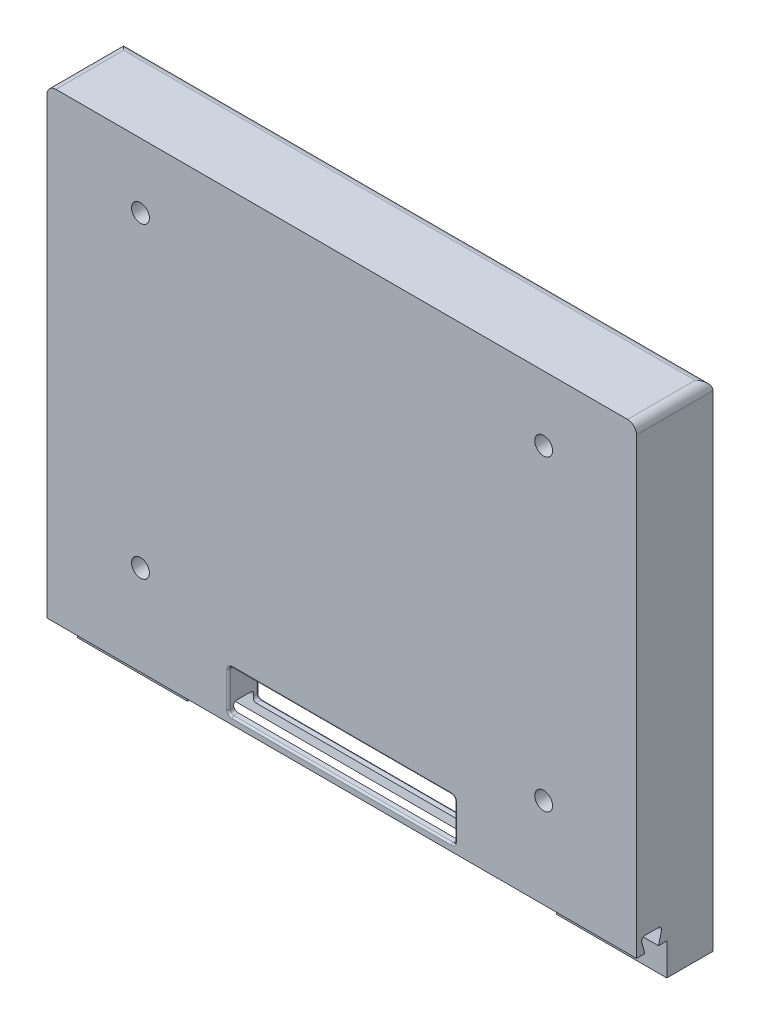
SolidWorks part; units mm, degrees
material "PLA"
ref_plane "Front Plane" through (0, 0, 0) normal (0, 0, 1) x (1, 0, 0)
ref_plane "Top Plane" through (0, 0, 0) normal (0, 1, 0) x (1, 0, 0)
ref_plane "Right Plane" through (0, 0, 0) normal (1, 0, 0) x (0, 0, -1)
sketch "Sketch1" plane through (0, 0, 0) normal (0, 0, 1) x (1, 0, 0)
  line L0 (0, 0) -> (0, -138.8145) construction
  line L1 (-82.55, -90.8019) -> (82.55, -90.8019)
  line L2 (-82.55, -90.8019) -> (-82.55, 9.1981)
  line L3 (-82.55, 9.1981) -> (82.55, 9.1981)
  line L4 (82.55, -90.8019) -> (82.55, 9.1981)
  point P7 (0, -90.8019)
  dimension "D1" = 165.1
  dimension "D2" = 100
extrude "Boss-Extrude1" add sketch "Sketch1" along normal blind 5
sketch "Sketch4" plane through (0, 0, 0) normal (0, 0, -1) x (-1, 0, 0)
  line L4 (-82.55, 9.1981) -> (-82.55, -90.8019)
  line L5 (-82.55, -90.8019) -> (82.55, -90.8019)
  line L6 (82.55, -90.8019) -> (82.55, 9.1981)
  line L7 (82.55, 9.1981) -> (-82.55, 9.1981)
  line L8 (-82.55, 9.1981) -> (-82.55, -90.8019)
  line L9 (-82.55, -90.8019) -> (82.55, -90.8019)
  line L10 (82.55, -90.8019) -> (82.55, 9.1981)
  line L11 (82.55, 9.1981) -> (-82.55, 9.1981)
  dimension "D1" = 0
extrude "Boss-Extrude2" add sketch "Sketch4" along normal blind 3.5
ref_plane "Plane1" through (-27.79, 0, 0) normal (-1, 0, 0) x (0, 0, 1)
sketch "Sketch10" plane through (0, -90.8019, 0) normal (0, -1, 0) x (1, 0, 0)
  line L4 (-82.55, 5) -> (-82.55, -3.5)
  line L5 (-82.55, -3.5) -> (82.55, -3.5)
  line L6 (82.55, -3.5) -> (82.55, 5)
  line L7 (82.55, 5) -> (-82.55, 5)
  line L8 (-82.55, 5) -> (-82.55, -3.5)
  line L9 (-82.55, -3.5) -> (82.55, -3.5)
  line L10 (82.55, -3.5) -> (82.55, 5)
  line L11 (82.55, 5) -> (-82.55, 5)
  dimension "D1" = 0
extrude "Boss-Extrude4" add sketch "Sketch10" along normal blind 17
sketch "Sketch11" plane through (0, 0, -3.5) normal (0, 0, -1) x (-1, 0, 0)
  line L0 (0, 9.1981) -> (0, -107.8019) construction
  line L1 (82.55, 9.1981) -> (-82.55, 9.1981) construction
  line L2 (82.55, -107.8019) -> (-82.55, -107.8019) construction
  line L3 (-82.55, -49.3019) -> (82.55, -49.3019) construction
  line L4 (-82.55, 9.1981) -> (-82.55, -107.8019) construction
  line L5 (82.55, -107.8019) -> (82.55, 9.1981) construction
  line L7 (-51.7, -3.8519) -> (51.7, -3.8519)
  line L8 (-51.7, -3.8519) -> (-51.7, -94.7519)
  line L9 (-51.7, -94.7519) -> (51.7, -94.7519)
  line L10 (51.7, -3.8519) -> (51.7, -94.7519)
  point P16 (0, -3.8519)
  point P17 (-51.7, -49.3019)
  dimension "D1" = 103.4
  dimension "D2" = 90.9
extrude "Cut-Extrude6" cut sketch "Sketch11" against normal blind 6
sketch "Sketch12" plane through (0, 0, -3.5) normal (0, 0, -1) x (-1, 0, 0)
  line L0 (82.55, -107.8019) -> (82.55, 9.1981) construction
  line L1 (-82.55, 9.1981) -> (82.55, 9.1981)
  line L2 (-82.55, 9.1981) -> (-82.55, -3.8519)
  line L3 (-82.55, -3.8519) -> (82.55, -3.8519)
  line L4 (82.55, 9.1981) -> (82.55, -3.8519)
  line L5 (51.7, -3.8519) -> (-51.7, -3.8519) construction
  dimension "D1" = 0
extrude "Boss-Extrude5" add sketch "Sketch12" along normal blind 12.95
sketch "Sketch13" plane through (0, 9.1981, 0) normal (0, 1, 0) x (1, 0, 0)
  line L0 (82.55, -5) -> (82.55, 16.45) construction
  line L1 (-82.55, 16.45) -> (82.55, 16.45)
  line L2 (-82.55, 16.45) -> (-82.55, -5)
  line L3 (-82.55, -5) -> (82.55, -5)
  line L4 (82.55, 16.45) -> (82.55, -5)
  dimension "D1" = 21.45
extrude "Boss-Extrude6" add sketch "Sketch13" along normal blind 9.75
sketch "Sketch14" plane through (0, 0, -3.5) normal (0, 0, -1) x (-1, 0, 0)
  line L0 (-51.7, -106.5019) -> (-51.7, -119.5519)
  line L7 (-82.55, -3.8519) -> (-82.55, -119.5519)
  line L10 (-82.55, -3.8519) -> (82.55, -3.8519) construction
  line L16 (-51.7, -3.8519) -> (-82.55, -3.8519)
  line L23 (-51.7, -106.5019) -> (-51.7, -3.8519)
  line L24 (-82.55, -119.5519) -> (-51.7, -119.5519)
  line L26 (82.55, -119.5519) -> (51.7, -119.5519)
  line L27 (82.55, -119.5519) -> (82.55, -3.8519)
  line L28 (82.55, -3.8519) -> (51.7, -3.8519)
  line L29 (51.7, -119.5519) -> (51.7, -3.8519)
  dimension "D1" = 115.7
  dimension "D2" = 115.7
extrude "Boss-Extrude7" add sketch "Sketch14" along normal up to surface (12.95 mm away) up to face at (0, 7.5481, -16.45)
sketch "Sketch15" plane through (0, 0, -16.45) normal (0, 0, -1) x (-1, 0, 0)
  circle A0 centre (56.3625, -85.2719) radius 1.35 construction
  circle A1 centre (56.3625, 0.8106) radius 1.35 construction
  circle A2 centre (-56.5625, 0.8106) radius 1.35 construction
  circle A3 centre (-56.5625, -85.2719) radius 1.35 construction
  circle A4 centre (56.3625, -85.2719) radius 1.35
  circle A5 centre (56.3625, 0.8106) radius 1.35
  circle A6 centre (-56.5625, 0.8106) radius 1.35
  circle A7 centre (-56.5625, -85.2719) radius 1.35
extrude "Cut-Extrude7" cut sketch "Sketch15" against normal blind 8.65
sketch "Sketch16" plane through (0, 0, -7.8) normal (0, 0, -1) x (-1, 0, 0)
  circle A0 centre (56.3625, 0.8106) radius 2.5
  circle A1 centre (-56.5625, 0.8106) radius 2.5
  circle A2 centre (-56.5625, -85.2719) radius 2.5
  circle A3 centre (56.3625, -85.2719) radius 2.5
  dimension "D1" = 5
  dimension "D2" = 5
extrude "Cut-Extrude8" cut sketch "Sketch16" against normal through all
sketch "Sketch17" plane through (0, -107.8019, 0) normal (0, -1, 0) x (1, 0, 0)
  line L0 (82.55, -3.5) -> (82.55, 5) construction
  line L1 (-82.55, 5) -> (82.55, 5)
  line L2 (-82.55, 5) -> (-82.55, -3.5)
  line L3 (-82.55, -3.5) -> (82.55, -3.5)
  line L4 (82.55, 5) -> (82.55, -3.5)
  dimension "D1" = 8.5
fillet "Fillet1" radius 2.5 3 edges at (82.55, 18.9481, -5.725) (-82.55, 18.9481, -5.725) (0, 18.9481, -16.45)
extrude "Boss-Extrude9" add sketch "Sketch17" along normal blind 2.75
sketch "Sketch20" plane through (82.55, 0, 0) normal (1, 0, 0) x (0, 0, -1)
  line L0 (1.1553, -110.5519) -> (2.0307, -107.2849)
  line L1 (1.1614, -106.1519) -> (-2.6614, -106.1519)
  line L2 (-3.5307, -107.2849) -> (-2.6553, -110.5519)
  line L3 (1.1553, -110.5519) -> (-2.6553, -110.5519)
  arc A0 (2.0307, -107.2849) -> (1.1614, -106.1519) centre (1.1614, -107.0519) ccw
  arc A1 (-2.6614, -106.1519) -> (-3.5307, -107.2849) centre (-2.6614, -107.0519) ccw
  point P2 (1.1449, -110.5908)
  point P19 (-2.6449, -110.5908)
extrude "Cut-Extrude9" cut sketch "Sketch20" against normal through all
sketch "Sketch21" plane through (0, -119.5519, 0) normal (0, -1, 0) x (1, 0, 0)
  line L0 (-82.55, -9.975) -> (-51.7, -9.975) construction
  line L1 (-82.55, -16.45) -> (-82.55, -3.5) construction
  line L2 (-51.7, -16.45) -> (-51.7, -3.5) construction
  line L3 (51.7, -9.975) -> (82.55, -9.975) construction
  line L4 (51.7, -16.45) -> (51.7, -3.5) construction
  line L5 (82.55, -16.45) -> (82.55, -3.5) construction
  circle A0 centre (-67.125, -9.975) radius 1.35
  circle A1 centre (67.125, -9.975) radius 1.35
  dimension "D1" = 2.7
  dimension "D2" = 2.7
extrude "Cut-Extrude10" cut sketch "Sketch21" against normal blind 17.5
sketch "Sketch22" plane through (0, 0, -3.5) normal (0, 0, -1) x (-1, 0, 0)
  line L0 (-51.7, -102.6519) -> (51.7, -102.6519) construction
  line L3 (-31.7, -108.5519) -> (31.7, -108.5519)
  line L4 (51.7, -94.7519) -> (-51.7, -94.7519)
  line L5 (-51.7, -94.7519) -> (-51.7, -110.5519)
  line L6 (-51.7, -110.5519) -> (51.7, -110.5519)
  line L7 (51.7, -110.5519) -> (51.7, -94.7519)
  line L8 (51.7, -94.7519) -> (-51.7, -94.7519) construction
  line L9 (-51.7, -94.7519) -> (-51.7, -110.5519) construction
  line L10 (-51.7, -110.5519) -> (51.7, -110.5519) construction
  line L11 (51.7, -110.5519) -> (51.7, -94.7519) construction
  line L12 (-31.7, -108.5519) -> (-31.7, -96.7519)
  line L13 (-31.7, -96.7519) -> (31.7, -96.7519)
  line L14 (31.7, -108.5519) -> (31.7, -96.7519)
  dimension "D2" = 20
  dimension "D3" = 20
  dimension "D4" = 2
  dimension "D5" = 2
  dimension "D1" = 0
extrude "Cut-Extrude11" cut sketch "Sketch22" against normal blind 10
fillet "Fillet2" radius 1 6 edges at (-31.7, -108.5519, 4.0956) (-31.7, -108.5519, -2.5956) (31.7, -108.5519, -2.5956) (31.7, -108.5519, 4.0956) (-31.7, -96.7519, 0.75) (31.7, -96.7519, 0.75)
fillet "Fillet3" radius 0.5 13 edges at (31.4071, -108.2591, 5) (31.7, -102.6519, 5) (31.4071, -97.0448, 5) (31.4071, -97.0448, -3.5) (0, -96.7519, 5) (0, -96.7519, -3.5) (-31.4071, -97.0448, 5) (-31.4071, -97.0448, -3.5) (-31.7, -102.6519, 5) (-31.4071, -108.2591, 5) (0, -108.5519, 5) (-31.4071, -108.2591, -3.5) (31.4071, -108.2591, -3.5)
